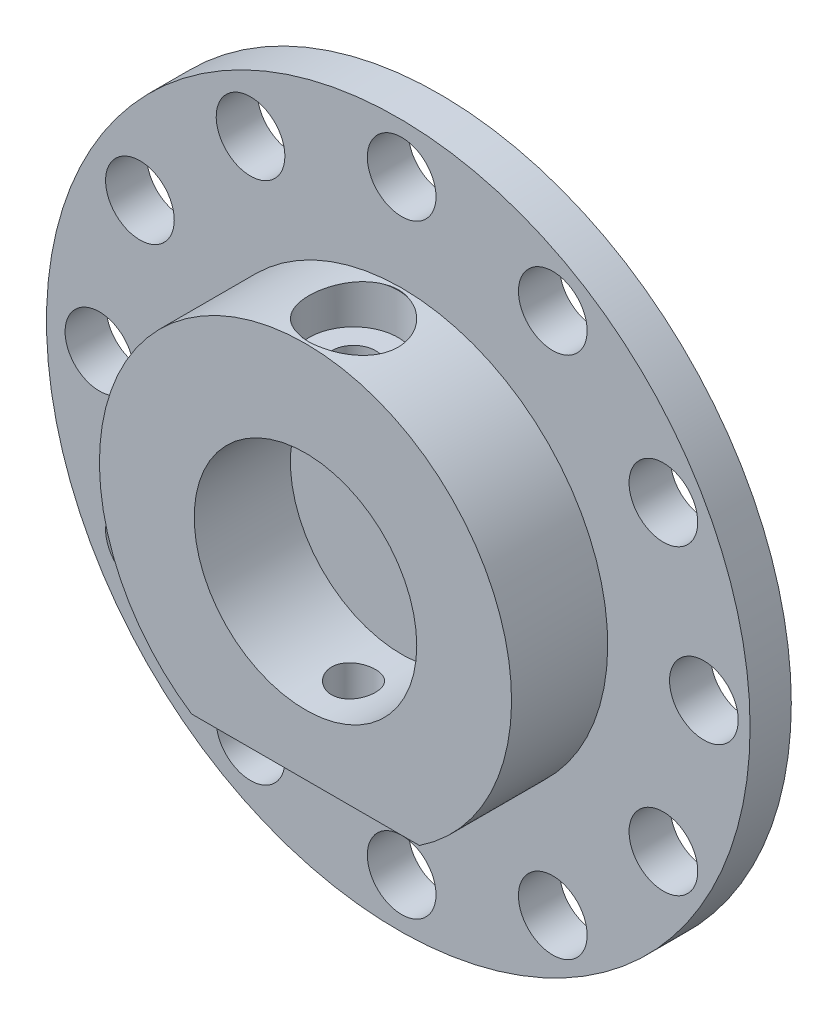
SolidWorks part; units mm, degrees
ref_plane "Front Plane" through (0, 0, 0) normal (0, 0, 1) x (1, 0, 0)
ref_plane "Top Plane" through (0, 0, 0) normal (0, 1, 0) x (1, 0, 0)
ref_plane "Right Plane" through (0, 0, 0) normal (1, 0, 0) x (0, 0, -1)
sketch "Sketch1" plane through (0, 0, 0) normal (0, 0, 1) x (1, 0, 0)
  circle A0 centre (-0.2449, 0) radius 25.6087
extrude "Boss-Extrude1" add sketch "Sketch1" along normal blind 3
sketch "Sketch2" plane through (0, 0, 3) normal (0, 0, 1) x (1, 0, 0)
  line L0 (0, 0) -> (0, -12.5) construction
  line L1 (8.2916, -12.5) -> (-8.2916, -12.5)
  arc A1 (8.2916, -12.5) -> (-8.2916, -12.5) centre (0, 0) ccw
  circle A3 centre (0, 0) radius 8.1
  dimension "D1" = 16.2
  dimension "D2" = 12.5
extrude "Boss-Extrude2" add sketch "Sketch2" along normal blind 7
ref_plane "Plane1" through (0, 15, 0) normal (0, 1, 0) x (1, 0, 0)
sketch "Sketch3" plane through (0, 15, 0) normal (0, 1, 0) x (1, 0, 0)
  line L0 (0, -3) -> (0, -10) construction
  line L1 (-15, -3) -> (15, -3) construction
  line L2 (-15, -10) -> (15, -10) construction
  circle A0 centre (0, -6.5) radius 1.75
  point P6 (0, -6.5)
  dimension "D1" = 3.5
hole_wizard "CBORE for M3 SHCS1" positions "Sketch3" profile "Sketch4" counterbore size "M3" standard "ANSI Metric" end condition through all
sketch "Sketch4" plane through (0, 15, 6.5) normal (1, 0, 0) x (0, 0, 1)
  line L0 (0, 0) -> (0, 40.6087)
  line L1 (0, 40.6087) -> (1.6, 40.6087)
  line L3 (1.6, 40.6087) -> (1.6, 3)
  line L4 (3.25, 3) -> (1.6, 3)
  line L5 (3.25, 3) -> (3.25, 0.025)
  line L6 (3.25, 0.025) -> (3.275, 0)
  line L7 (3.275, 0) -> (0, 0)
  line L8 (-3.25, 0.025) -> (-3.275, 0) construction
  line L11 (0, -6.35) -> (0, 107.95) construction
  dimension "Thru Hole Dia." = 3.2
  dimension "Thru Hole Depth" = 40.6087
  dimension "C'Bore Dia." = 6.5
  dimension "C'Bore Depth" = 3
  dimension "Near C'Sink Dia." = 6.55
  dimension "Near C'Sink Angle" = 90
sketch "Sketch6" plane through (0, 0, 10) normal (0, 0, 1) x (1, 0, 0)
  line L0 (0, 0) -> (0, -12.5) construction
  line L1 (8.2916, -12.5) -> (-8.2916, -12.5)
  circle A0 centre (0, 0) radius 15 construction
  arc A1 (-8.2916, -12.5) -> (8.2916, -12.5) centre (0, 0) ccw
  dimension "D1" = 12.5
sketch "Sketch7" plane through (0, 0, 0) normal (0, 0, -1) x (-1, 0, 0)
  line L0 (0, 0) -> (0, 22) construction
  circle A0 centre (0, 22) radius 2.5
  dimension "D1" = 22
extrude "Cut-Extrude1" cut sketch "Sketch7" against normal blind 10
pattern_circular "CirPattern1" count 12 every 30 about axis through (0, 0, 0) along (0, 0, 1) of "Cut-Extrude1"
